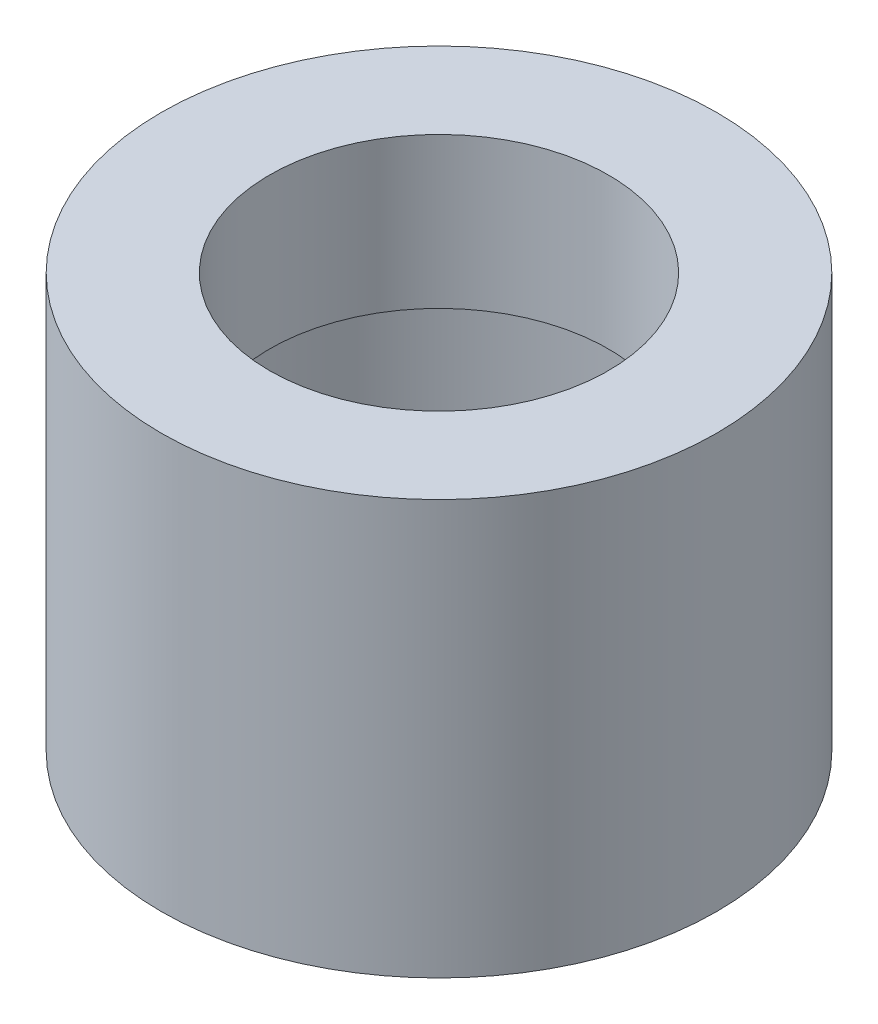
SolidWorks part; units mm, degrees
ref_plane "Front Plane" through (0, 0, 0) normal (0, 0, 1) x (1, 0, 0)
ref_plane "Top Plane" through (0, 0, 0) normal (0, 1, 0) x (1, 0, 0)
ref_plane "Right Plane" through (0, 0, 0) normal (1, 0, 0) x (0, 0, -1)
sketch "Sketch1" plane through (0, 0, 0) normal (0, 1, 0) x (1, 0, 0)
  circle A0 centre (0, 0) radius 14.75
  circle A1 centre (0, 0) radius 13
  dimension "D1" = 26
  dimension "D2" = 29.5
extrude "Boss-Extrude1" add sketch "Sketch1" against normal mid plane 22
sketch "Sketch2" plane through (0, 11, 0) normal (0, 1, 0) x (1, 0, 0)
  circle A0 centre (0, 0) radius 13
  circle A1 centre (0, 0) radius 9
  dimension "D1" = 26
  dimension "D2" = 18
extrude "Boss-Extrude2" add sketch "Sketch2" against normal blind 8
